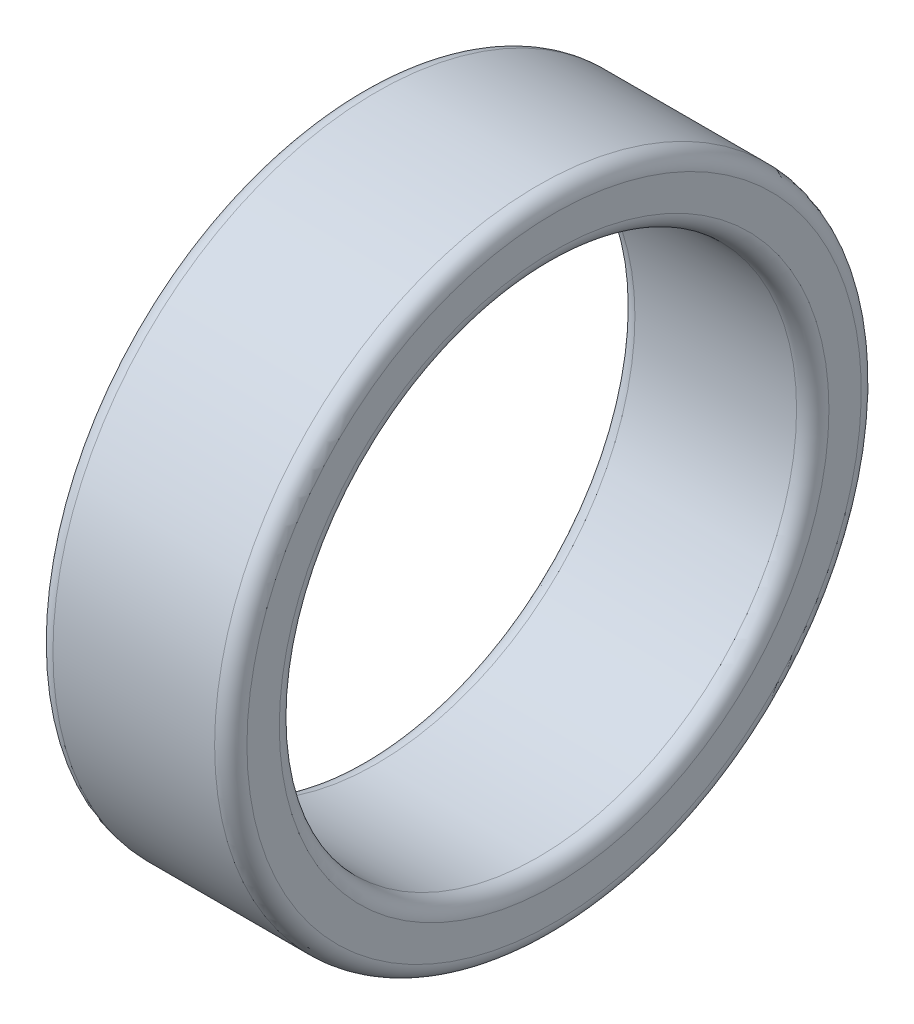
SolidWorks part; units mm, degrees
ref_plane "Alzado" through (0, 0, 0) normal (0, 0, 1) x (1, 0, 0)
ref_plane "Planta" through (0, 0, 0) normal (0, 1, 0) x (1, 0, 0)
ref_plane "Vista lateral" through (0, 0, 0) normal (1, 0, 0) x (0, 0, -1)
sketch "Croquis1" plane through (0, 0, 0) normal (0, 1, 0) x (1, 0, 0)
  line L0 (0, 0) -> (0, 4) construction
  line L1 (0, 0) -> (9.027, 0) construction
  line L3 (1.5, 4.25) -> (1.5, 4.75)
  line L4 (1.25, 5) -> (-1.25, 5)
  line L5 (-1.5, 4.75) -> (-1.5, 4.25)
  line L6 (-1.25, 4) -> (1.25, 4)
  arc A0 (1.5, 4.75) -> (1.25, 5) centre (1.25, 4.75) ccw
  arc A1 (1.5, 4.25) -> (1.25, 4) centre (1.25, 4.25) cw
  arc A2 (-1.5, 4.75) -> (-1.25, 5) centre (-1.25, 4.75) cw
  arc A3 (-1.5, 4.25) -> (-1.25, 4) centre (-1.25, 4.25) ccw
  point P10 (1.5, 5)
  dimension "D5" = 0.25
  dimension "D1" = 0.25
revolve "Revolución1" add sketch "Croquis1" angle 360 about L1
